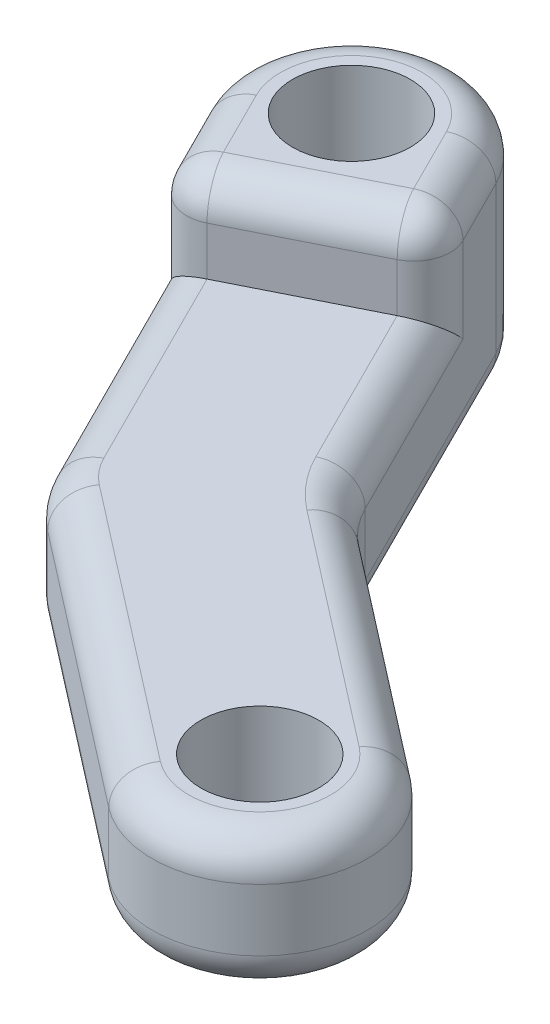
SolidWorks part; units mm, degrees
ref_plane "Front Plane" through (0, 0, 0) normal (0, 0, 1) x (1, 0, 0)
ref_plane "Top Plane" through (0, 0, 0) normal (0, 1, 0) x (1, 0, 0)
ref_plane "Right Plane" through (0, 0, 0) normal (1, 0, 0) x (0, 0, -1)
sketch "Sketch1" plane through (0, 0, 0) normal (0, 1, 0) x (1, 0, 0)
  line L26 (-14.1296, 12.6954) -> (-9.9761, 4.3964)
  line L27 (-9.1294, 3.3665) -> (-1.7902, -2.3132)
  line L28 (-8.8983, 15.3136) -> (-5.3415, 8.2069)
  line L29 (-4.4948, 7.177) -> (1.7902, 2.3132)
  line L30 (-9.6107, 3.8338) -> (-4.976, 7.6443) construction
  line L31 (-11.514, 14.0045) -> (0, 0) construction
  circle A14 centre (-11.514, 14.0045) radius 1.6
  circle A15 centre (0, 0) radius 1.6
  arc A17 (-1.7902, -2.3132) -> (1.7902, 2.3132) centre (0, 0) ccw
  arc A18 (-14.1296, 12.6954) -> (-8.8983, 15.3136) centre (-11.514, 14.0045) cw
  arc A19 (-5.3415, 8.2069) -> (-4.4948, 7.177) centre (-2.6587, 9.5495) ccw
  arc A20 (-9.9761, 4.3964) -> (-9.1294, 3.3665) centre (-7.2934, 5.7391) ccw
  point P3 (-7.2934, 5.7391)
  point P17 (-8.1974, 6.4387)
  point P20 (-5.757, 7.0022)
  dimension "D4" = 5.85
  dimension "D1" = 3
  dimension "D2" = 18.13
  dimension "D3" = 5.85
extrude "Boss-Extrude1" add sketch "Sketch1" along normal blind 6
fillet "Fillet2" radius 1 16 edges at (-4.976, 0, -7.6443) (-4.976, 6, -7.6443) (-1.3523, 0, -4.7451) (2.3132, 0, 1.7902) (-5.4598, 0, -0.5267) (-9.6107, 0, -3.8338) (-12.0529, 0, -8.5459) (-12.8231, 0, -16.6202) (-7.1199, 0, -11.7602) (-1.3523, 6, -4.7451) (2.3132, 6, 1.7902) (-5.4598, 6, -0.5267) (-9.6107, 6, -3.8338) (-12.0529, 6, -8.5459) (-12.8231, 6, -16.6202) (-7.1199, 6, -11.7602)
sketch "Sketch3" plane through (0, 6, 0) normal (0, 1, 0) x (1, 0, 0)
  line L0 (-8.8983, 15.3136) -> (-5.3415, 8.2069) construction
  line L1 (-4.4948, 7.177) -> (1.7902, 2.3132) construction
  line L2 (-1.7902, -2.3132) -> (-9.1294, 3.3665) construction
  line L3 (-9.9761, 4.3964) -> (-14.1296, 12.6954) construction
  line L4 (-6.2357, 7.7593) -> (-9.7925, 14.866)
  line L5 (-13.2354, 13.1429) -> (-9.0819, 4.844)
  line L6 (-8.5174, 4.1574) -> (-1.1781, -1.5224)
  line L7 (1.1781, 1.5224) -> (-5.1068, 6.3862)
  line L8 (-6.2357, 7.7593) -> (-8.4498, 12.1833)
  line L9 (-11.8927, 10.4602) -> (-9.0819, 4.844)
  line L10 (-8.5174, 4.1574) -> (-1.1781, -1.5224)
  line L11 (1.1781, 1.5224) -> (-5.1068, 6.3862)
  line L12 (-7.5556, 12.6308) -> (-5.3415, 8.2069)
  line L13 (-4.4948, 7.177) -> (1.7902, 2.3132)
  line L14 (-1.7902, -2.3132) -> (-9.1294, 3.3665)
  line L15 (-9.9761, 4.3964) -> (-12.787, 10.0126)
  line L16 (-12.787, 10.0126) -> (-7.5556, 12.6308)
  circle A0 centre (-11.514, 14.0045) radius 1.6 construction
  circle A2 centre (0, 0) radius 1.6 construction
  circle A3 centre (0, 0) radius 1.6
  arc A4 (-9.7925, 14.866) -> (-13.2354, 13.1429) centre (-11.514, 14.0045) ccw
  arc A5 (-9.0819, 4.844) -> (-8.5174, 4.1574) centre (-7.2934, 5.7391) ccw
  arc A6 (-1.1781, -1.5224) -> (1.1781, 1.5224) centre (0, 0) ccw
  arc A7 (-6.2357, 7.7593) -> (-5.1068, 6.3862) centre (-2.6587, 9.5495) ccw
  arc A9 (-9.0819, 4.844) -> (-8.5174, 4.1574) centre (-7.2934, 5.7391) ccw
  arc A10 (-1.1781, -1.5224) -> (1.1781, 1.5224) centre (0, 0) ccw
  arc A11 (-6.2357, 7.7593) -> (-5.1068, 6.3862) centre (-2.6587, 9.5495) ccw
  arc A12 (-5.3415, 8.2069) -> (-4.4948, 7.177) centre (-2.6587, 9.5495) ccw construction
  arc A13 (-1.7902, -2.3132) -> (1.7902, 2.3132) centre (0, 0) ccw construction
  arc A14 (-9.9761, 4.3964) -> (-9.1294, 3.3665) centre (-7.2934, 5.7391) ccw construction
  arc A15 (-5.3415, 8.2069) -> (-4.4948, 7.177) centre (-2.6587, 9.5495) ccw
  arc A16 (-1.7902, -2.3132) -> (1.7902, 2.3132) centre (0, 0) ccw
  arc A17 (-9.9761, 4.3964) -> (-9.1294, 3.3665) centre (-7.2934, 5.7391) ccw
  line M11 (-6.2357, 7.7593) -> (-9.7925, 14.866)
  line M13 (-13.2354, 13.1429) -> (-9.0819, 4.844)
  arc M14 (-9.0819, 4.844) -> (-8.5174, 4.1574) centre (-7.2934, 5.7391) ccw
  line M15 (-8.5174, 4.1574) -> (-1.1781, -1.5224)
  arc M16 (-1.1781, -1.5224) -> (1.1781, 1.5224) centre (0, 0) ccw
  line M17 (1.1781, 1.5224) -> (-5.1068, 6.3862)
  arc M18 (-5.1068, 6.3862) -> (-6.2357, 7.7593) centre (-2.6587, 9.5495) cw
  circle M20 centre (0, 0) radius 1.6
  dimension "D2" = 3
  dimension "D1" = 0
extrude "Cut-Extrude1" cut sketch "Sketch3" against normal blind 2.3175 contours L16 M13 M14 M15 M16 M17 M18 M11 M20 | L15 A17 L14 A16 L13 A15 L12 L16 M11 M18 M17 M16 M15 M14 M13
fillet "Fillet3" radius 1 7 edges at (-11.3816, 3.6825, -7.2045) (-9.6107, 3.6825, -3.8338) (-5.4598, 3.6825, -0.5267) (-6.4485, 3.6825, -10.4188) (-4.976, 3.6825, -7.6443) (-1.3523, 3.6825, -4.7451) (2.3132, 3.6825, 1.7902)
fillet "Fillet4" radius 1 5 edges at (-12.525, 5.7071, -10.1437) (-10.1713, 6, -11.3217) (-7.8175, 5.7071, -12.4998) (-12.787, 3.8413, -10.0126) (-7.5556, 3.8413, -12.6308)
